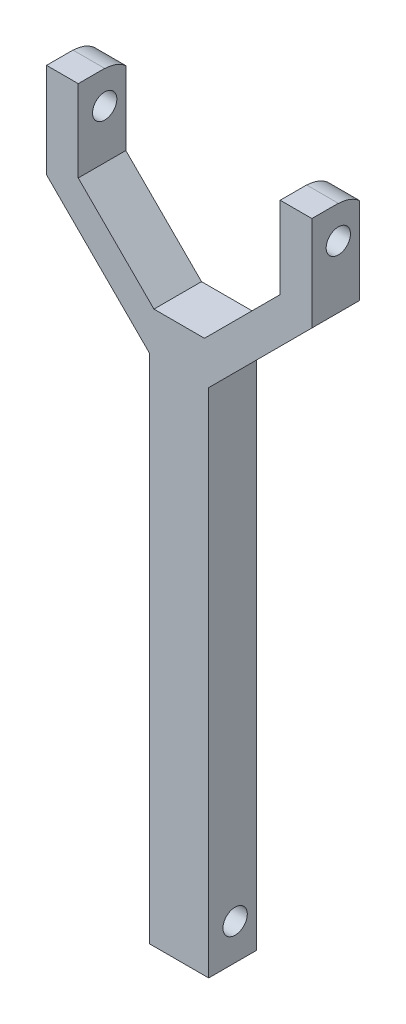
SolidWorks part; units mm, degrees
ref_plane "前视基准面" through (0, 0, 0) normal (0, 0, 1) x (1, 0, 0)
ref_plane "上视基准面" through (0, 0, 0) normal (0, 1, 0) x (1, 0, 0)
ref_plane "右视基准面" through (0, 0, 0) normal (1, 0, 0) x (0, 0, -1)
sketch "草图1" plane through (0, 0, 0) normal (0, 0, 1) x (1, 0, 0)
  line L0 (-3.6631, -33.4009) -> (1.9146, -33.4009)
  line L1 (1.9146, -33.4009) -> (1.9146, 14.9603)
  line L2 (1.9146, 14.9603) -> (11.6757, 24.7215)
  line L3 (11.6757, 24.7215) -> (11.6757, 33.6923)
  line L4 (11.6757, 33.6923) -> (8.6757, 33.6923)
  line L5 (8.6757, 33.6923) -> (8.6757, 25.9641)
  line L6 (8.6757, 25.9641) -> (1.5148, 18.8032)
  line L7 (1.5148, 18.8032) -> (-3.2634, 18.8032)
  line L8 (-3.2634, 18.8032) -> (-10.4243, 25.9641)
  line L9 (-10.4243, 25.9641) -> (-10.4243, 33.6923)
  line L10 (-10.4243, 33.6923) -> (-13.4243, 33.6923)
  line L11 (-13.4243, 33.6923) -> (-13.4243, 24.7215)
  line L12 (-13.4243, 24.7215) -> (-3.6631, 14.9603)
  line L13 (-3.6631, 14.9603) -> (-3.6631, -33.4009)
extrude "凸台-拉伸1" add sketch "草图1" along normal blind 4.5
sketch "草图2" plane through (0, 0, 0) normal (1, 0, 0) x (0, 0, -1)
  circle A0 centre (-2, -29.9935) radius 1.15
  circle A1 centre (-2, 30.6105) radius 1.15
extrude "切除-拉伸1" cut sketch "草图2" against normal blind 100 and the other way blind 100
sketch "草图3" plane through (-10.4243, 0, 0) normal (1, 0, 0) x (0, 0, -1)
  line L0 (-2, 33.6653) -> (-2, 37.691)
  line L1 (1.0548, 30.6105) -> (5.0805, 30.6105)
  circle A0 centre (-2, 30.6105) radius 3.0548 construction
  circle A1 centre (-2, 30.6105) radius 7.0805 construction
  arc A2 (1.0548, 30.6105) -> (-2, 33.6653) centre (-2, 30.6105) ccw
  arc A3 (5.0805, 30.6105) -> (-2, 37.691) centre (-2, 30.6105) ccw
extrude "切除-拉伸2" cut sketch "草图3" against normal blind 10 and the other way blind 100
